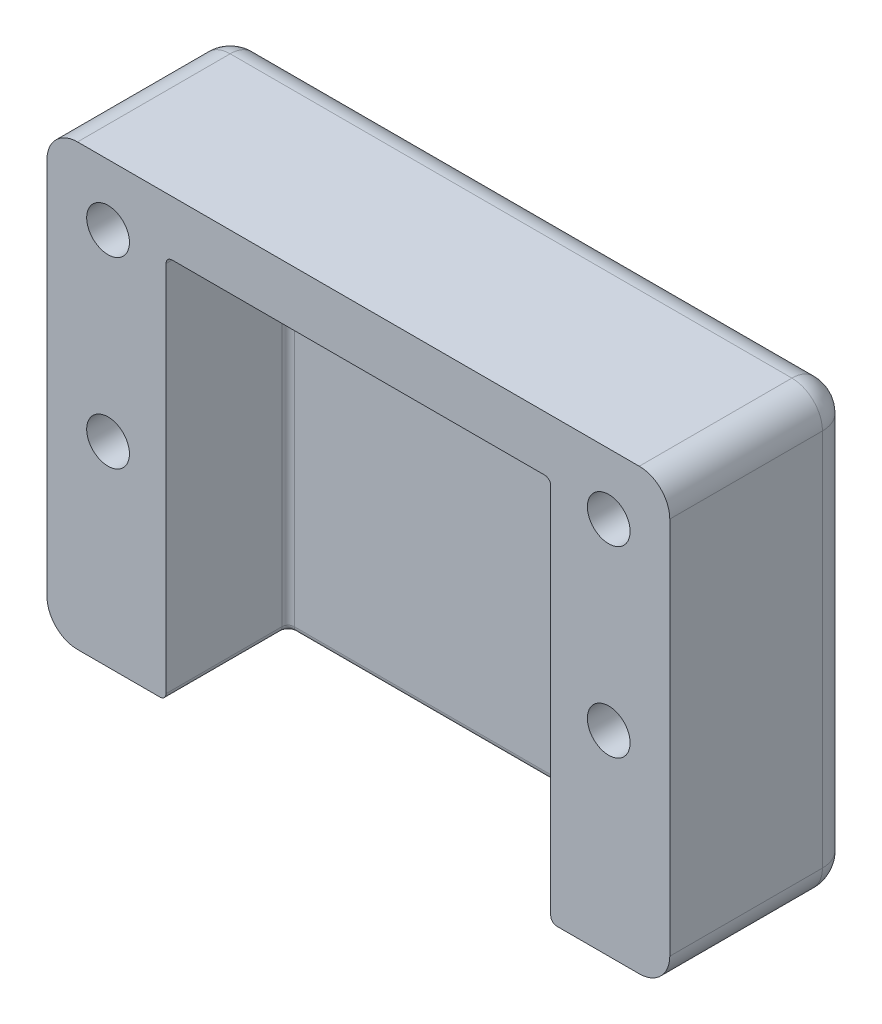
SolidWorks part; units mm, degrees
ref_plane "Front Plane" through (0, 0, 0) normal (0, 0, 1) x (1, 0, 0)
ref_plane "Top Plane" through (0, 0, 0) normal (0, 1, 0) x (1, 0, 0)
ref_plane "Right Plane" through (0, 0, 0) normal (1, 0, 0) x (0, 0, -1)
sketch "Sketch1" plane through (0, 0, 0) normal (0, 0, 1) x (1, 0, 0)
  line L0 (0, 0) -> (51, 0)
  line L1 (51, 0) -> (51, 36)
  line L2 (51, 36) -> (0, 36)
  line L3 (0, 36) -> (0, 0)
  dimension "D1" = 36
  dimension "D2" = 51
extrude "Boss-Extrude1" add sketch "Sketch1" along normal blind 15
sketch "Sketch2" plane through (0, 0, 15) normal (0, 0, 1) x (1, 0, 0)
  line L0 (9.75, 0) -> (9.75, 31.5)
  line L1 (0, 0) -> (51, 0) construction
  line L2 (9.75, 31.5) -> (41.25, 31.5)
  line L3 (41.25, 31.5) -> (41.25, 0)
  line L4 (41.25, 0) -> (9.75, 0)
  line L5 (0, 36) -> (0, 0) construction
  line L6 (51, 0) -> (51, 36) construction
  line L7 (51, 36) -> (0, 36) construction
  dimension "D1" = 9.75
  dimension "D2" = 4.5
  dimension "D3" = 9.75
extrude "Cut-Extrude1" cut sketch "Sketch2" against normal blind 10
sketch "Sketch3" plane through (0, 0, 15) normal (0, 0, 1) x (1, 0, 0)
  line L0 (0, 36) -> (0, 0) construction
  line L1 (51, 36) -> (0, 36) construction
  line L2 (51, 0) -> (51, 36) construction
  circle A0 centre (5, 31) radius 1.75
  circle A1 centre (5, 16) radius 1.75
  circle A2 centre (46, 31) radius 1.75
  circle A3 centre (46, 16) radius 1.75
  dimension "D1" = 3.5
  dimension "D2" = 3.5
  dimension "D3" = 3.5
  dimension "D4" = 3.5
  dimension "D6" = 5
  dimension "D9" = 15
  dimension "D10" = 15
  dimension "D5" = 5
  dimension "D7" = 5
  dimension "D8" = 5
extrude "Cut-Extrude2" cut sketch "Sketch3" against normal through all
fillet "Fillet1" radius 0.5 8 edges at (9.75, 0, 10) (25.5, 0, 5) (41.25, 0, 10) (41.25, 31.5, 10) (9.75, 31.5, 10) (9.75, 15.75, 5) (41.25, 15.75, 5) (25.5, 31.5, 5)
fillet "Fillet2" radius 2.5 8 edges at (25.5, 0, 0) (0, 18, 0) (0, 36, 7.5) (51, 36, 7.5) (25.5, 36, 0) (51, 18, 0) (51, 0, 7.5) (0, 0, 7.5)
